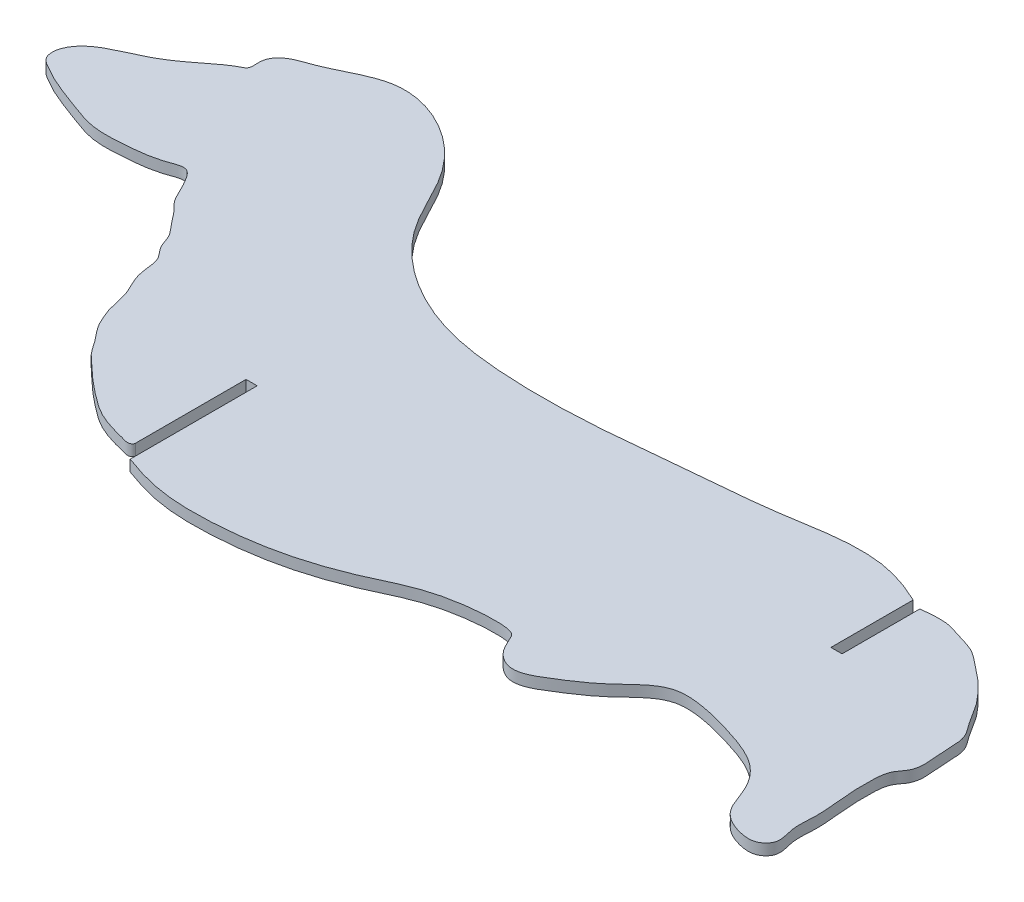
SolidWorks part; units mm, degrees
ref_plane "Спереди" through (0, 0, 0) normal (0, 0, 1) x (1, 0, 0)
ref_plane "Сверху" through (0, 0, 0) normal (0, 1, 0) x (1, 0, 0)
ref_plane "Справа" through (0, 0, 0) normal (1, 0, 0) x (0, 0, -1)
sketch "Эскиз1" plane through (0, 0, 0) normal (0, 1, 0) x (1, 0, 0)
  line L0 (67.558, 140.4457) -> (334.2247, 140.4457) construction
  line L1 (158.7589, 127.6455) -> (162.7589, 127.6455)
  line L2 (158.7589, 127.6455) -> (158.7589, 87.8711)
  line L3 (162.7589, 127.6455) -> (162.7589, 82.0276)
  line L4 (347.1549, 178.835) -> (347.1549, 149.3029)
  line L5 (347.1549, 149.3029) -> (351.1549, 149.3029)
  line L6 (351.1549, 149.3029) -> (351.1549, 177.2129)
  spline S0 degree 3 poles (347.1549, 178.835) (342.2936, 181.1864) (331.7324, 185.1532) (314.9561, 185.039) (301.512, 182.5485) (288.3693, 180.7125) (275.6398, 179.5188) (261.9069, 178.3317) (236.9029, 175.6072) (210.1193, 174.213) (171.5942, 179.3824) (143.2439, 196.9515) (132.1247, 225.9467) (116.5956, 241.8811) (93.2745, 249.602) (77.8882, 238.7147) (65.9008, 235.4102) (61.5756, 230.2004) (63.1087, 225.0454) (58.2569, 222.6446) (51.9613, 217.7652) (40.1028, 208.403) (25.0001, 204.5842) (21.9848, 195.2729) (22.3434, 191.414) (26.573, 188.9341) (32.4195, 185.6328) (41.394, 182.5804) (52.2542, 177.9249) (64.9559, 178.9248) (74.5178, 179.7641) (82.752, 183.5138) (85.9497, 178.7725) (88.1853, 174.7301) (90.0907, 170.108) (94.2337, 166.565) (96.9707, 162.3052) (100.8343, 158.438) (101.7583, 153.261) (106.2349, 149.3629) (106.2213, 143.3112) (107.9177, 137.8529) (111.1154, 132.2556) (111.7173, 126.5311) (113.7625, 121.4177) (115.788, 116.9255) (119.6961, 112.7765) (122.5594, 107.8798) (126.8119, 104.3123) (131.2045, 99.9842) (137.8517, 94.7604) (144.6395, 89.6771) (154.3324, 87.3302) (154.6762, 87.2834) (158.493, 85.9403) (158.7998, 87.8721) (158.7589, 87.8711) knots 0 0 0 0 0.027871 0.05705 0.084881 0.098282 0.125273 0.150633 0.169162 0.25472 0.287217 0.369493 0.408005 0.444216 0.481764 0.521977 0.534426 0.545221 0.553498 0.555204 0.571843 0.594977 0.634375 0.637983 0.644972 0.652096 0.661528 0.680137 0.700473 0.721552 0.743317 0.753146 0.760747 0.768608 0.77804 0.785619 0.796197 0.804077 0.813062 0.82198 0.832552 0.842283 0.851406 0.865319 0.871224 0.879724 0.890433 0.900259 0.908606 0.918705 0.932164 0.951133 0.96681 0.969284 0.97587 1 1 1 1
  spline S1 degree 3 poles (162.7589, 82.0276) (174.0801, 77.7364) (187.3266, 76.2211) (208.5741, 77.6951) (225.7841, 81.3569) (244.0509, 88.2334) (258.8409, 96.6234) (284.4178, 98.3845) (287.1408, 94.0714) (288.874, 88.9384) (296.8101, 83.3275) (308.0596, 90.267) (319.3557, 97.7079) (329.2849, 109.3856) (343.6985, 108.0307) (356.2126, 104.4649) (369.0781, 99.8633) (376.5108, 89.7631) (378.8656, 79.1404) (387.5429, 75.2053) (394.3044, 74.6798) (398.9974, 79.1797) (396.0826, 85.981) (397.4017, 95.0694) (395.8727, 105.0633) (395.6421, 114.4105) (396.1122, 121.3344) (399.2679, 124.6426) (400.514, 128.4944) (400.1745, 132.1725) (399.834, 136.4118) (399.7143, 140.7567) (399.2788, 145.6812) (395.1035, 150.8245) (392.1184, 156.6546) (387.0584, 162.344) (382.722, 166.5577) (377.7648, 170.207) (373.1217, 174.2052) (363.9568, 176.2636) (360.8888, 178.4907) (351.1549, 177.2129) knots 0 0 0 0 0.03577 0.06272 0.088966 0.112043 0.14349 0.174363 0.179832 0.198175 0.221108 0.260436 0.304523 0.355898 0.38933 0.431438 0.480921 0.511393 0.545692 0.576182 0.593068 0.606431 0.628499 0.653092 0.693002 0.721356 0.742256 0.754376 0.762723 0.779364 0.788395 0.802584 0.820453 0.832717 0.863421 0.881695 0.903655 0.919958 0.939265 0.960992 1 1 1 1
extrude "Бобышка-Вытянуть1" add sketch "Эскиз1" along normal blind 4
